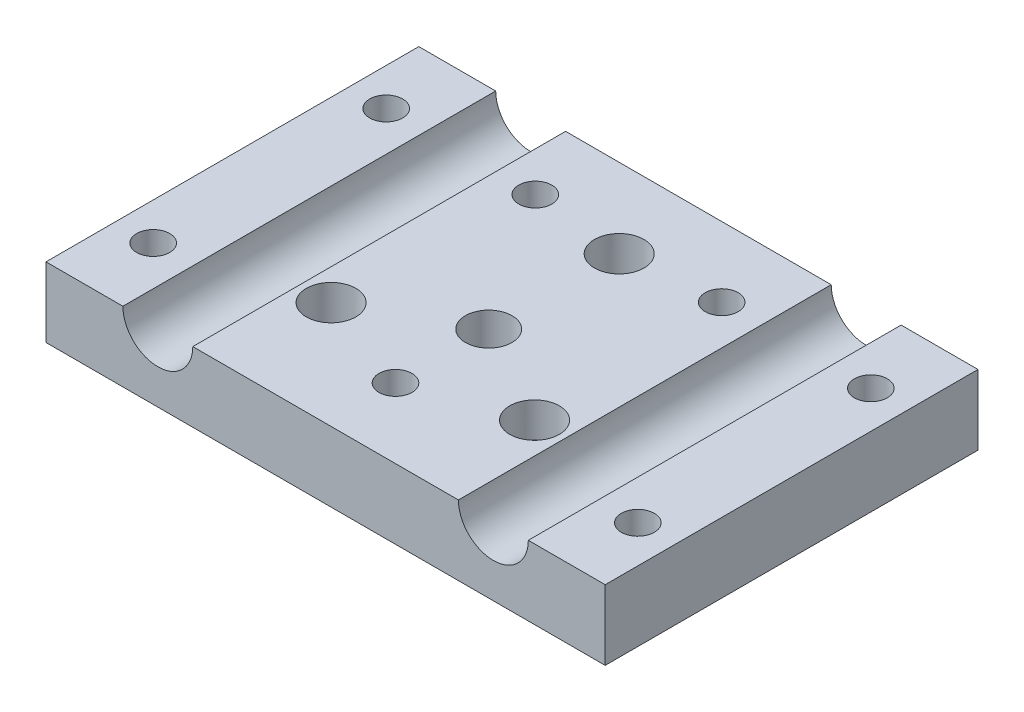
SolidWorks part; units mm, degrees
material "Copper"
ref_plane "Front Plane" through (0, 0, 0) normal (0, 0, 1) x (1, 0, 0)
ref_plane "Top Plane" through (0, 0, 0) normal (0, 1, 0) x (1, 0, 0)
ref_plane "Right Plane" through (0, 0, 0) normal (1, 0, 0) x (0, 0, -1)
sketch "Sketch1" plane through (0, 0, 0) normal (0, 1, 0) x (1, 0, 0)
  line L1 (-38.1, 25.4) -> (38.1, 25.4)
  line L2 (-38.1, 25.4) -> (-38.1, -25.4)
  line L3 (-38.1, -25.4) -> (38.1, -25.4)
  line L4 (38.1, 25.4) -> (38.1, -25.4)
  dimension "D1" = 50.8
  dimension "D2" = 76.2
  dimension "D3" = 38.1
  dimension "D4" = 25.4
extrude "Boss-Extrude1" add sketch "Sketch1" along normal blind 9.525
hole_wizard "1/4 Clearance Hole1" positions "Sketch3" profile "Sketch2" hole size "1/4" standard "ANSI Inch" end condition through all
sketch "Sketch3" plane through (0, 9.525, 0) normal (0, 1, 0) x (1, 0, 0)
  point P0 (0, 14.6101)
  point P2 (-13.8608, -10.7899)
  point P4 (13.8608, -10.7899)
  dimension "D1" = 10.7899
  dimension "D2" = 14.6101
  dimension "D3" = 13.8608
  dimension "D4" = 27.7216
sketch "Sketch2" plane through (0, 9.525, -14.6101) normal (1, 0, 0) x (0, 0, 1)
  line L0 (0, 0) -> (0, 9.525)
  line L1 (0, 9.525) -> (3.3782, 9.525)
  line L2 (3.3782, 9.525) -> (3.3782, 0)
  line L5 (3.3782, 0) -> (0, 0)
  line L11 (0, -6.35) -> (0, 107.95) construction
  dimension "Thru Hole Dia." = 6.7564
  dimension "Thru Hole Depth" = 9.525
sketch "Sketch4" plane through (0, 0, 25.4) normal (0, 0, 1) x (1, 0, 0)
  line L0 (-38.1, 9.525) -> (38.1, 9.525) construction
  line L1 (-27.6225, 9.525) -> (-18.0975, 9.525)
  line L2 (18.0975, 9.525) -> (27.6225, 9.525)
  arc A0 (-27.6225, 9.525) -> (-18.0975, 9.525) centre (-22.86, 9.525) ccw
  arc A1 (18.0975, 9.525) -> (27.6225, 9.525) centre (22.86, 9.525) ccw
  dimension "D1" = 4.7625
  dimension "D2" = 4.7625
  dimension "D3" = 22.86
  dimension "D4" = 22.86
extrude "Cut-Extrude1" cut sketch "Sketch4" against normal through all
sketch "Sketch5" plane through (0, 9.525, 0) normal (0, 1, 0) x (1, 0, 0)
  circle A0 centre (0, -3.175) radius 2.3813
  dimension "D1" = 3.175
  dimension "D2" = 4.7625
extrude "Cut-Extrude2" cut sketch "Sketch5" against normal through all
hole_wizard "#8 Clearance Hole1" positions "Sketch7" profile "Sketch6" hole size "#8" standard "ANSI Inch" end condition through all
sketch "Sketch7" plane through (0, 9.525, 0) normal (0, 1, 0) x (1, 0, 0)
  point P0 (-33.02, 15.875)
  point P2 (-33.02, -15.875)
  point P4 (33.02, -15.875)
  point P6 (33.02, 15.875)
  point P14 (-12.7, 15.875)
  point P16 (12.7, 15.875)
  point P18 (0, -15.875)
  dimension "D1" = 33.02
  dimension "D2" = 15.875
  dimension "D3" = 15.875
  dimension "D4" = 33.02
  dimension "D5" = 12.7
  dimension "D6" = 12.7
sketch "Sketch6" plane through (-33.02, 9.525, -15.875) normal (1, 0, 0) x (0, 0, 1)
  line L0 (0, 0) -> (0, 9.525)
  line L1 (0, 9.525) -> (2.2479, 9.525)
  line L2 (2.2479, 9.525) -> (2.2479, 0)
  line L5 (2.2479, 0) -> (0, 0)
  line L11 (0, -6.35) -> (0, 107.95) construction
  dimension "Thru Hole Dia." = 4.4958
  dimension "Thru Hole Depth" = 9.525
sketch "Sketch8" plane through (0, 0, 0) normal (0, -1, 0) x (1, 0, 0)
  line L0 (-17.2898, 4.8209) -> (-10.4318, 4.8209)
  line L1 (-10.4318, 4.8209) -> (-7.0028, 10.7601)
  line L2 (-7.0028, 10.7601) -> (-10.4318, 16.6993)
  line L3 (-10.4318, 16.6993) -> (-17.2898, 16.6993)
  line L4 (-17.2898, 16.6993) -> (-20.7188, 10.7601)
  line L5 (-20.7188, 10.7601) -> (-17.2898, 4.8209)
  line L6 (10.4318, 4.8209) -> (17.2898, 4.8209)
  line L7 (17.2898, 4.8209) -> (20.7188, 10.7601)
  line L8 (20.7188, 10.7601) -> (17.2898, 16.6993)
  line L9 (17.2898, 16.6993) -> (10.4318, 16.6993)
  line L10 (10.4318, 16.6993) -> (7.0028, 10.7601)
  line L11 (7.0028, 10.7601) -> (10.4318, 4.8209)
  line L12 (-3.429, -20.5791) -> (3.429, -20.5791)
  line L13 (3.429, -20.5791) -> (6.858, -14.6399)
  line L14 (6.858, -14.6399) -> (3.429, -8.7007)
  line L15 (3.429, -8.7007) -> (-3.429, -8.7007)
  line L16 (-3.429, -8.7007) -> (-6.858, -14.6399)
  line L17 (-6.858, -14.6399) -> (-3.429, -20.5791)
  circle A0 centre (-13.8608, 10.7899) radius 3.3782 construction
  circle A1 centre (13.8608, 10.7899) radius 3.3782 construction
  circle A2 centre (0, -14.6101) radius 3.3782 construction
  dimension "D1" = 6.858
  dimension "D2" = 120
  dimension "D3" = 11.8784
  dimension "D4" = 5.969
  dimension "D5" = 13.716
  dimension "D6" = 6.858
  dimension "D7" = 6.858
  dimension "D8" = 120
  dimension "D9" = 11.8784
  dimension "D10" = 5.969
  dimension "D11" = 6.858
  dimension "D12" = 6.858
  dimension "D13" = 120
  dimension "D14" = 11.8784
  dimension "D15" = 5.969
  dimension "D16" = 6.858
extrude "Cut-Extrude3" cut sketch "Sketch8" against normal blind 4.7625
sketch "Sketch9" plane through (0, 0, 0) normal (0, -1, 0) x (1, 0, 0)
  line L0 (-37.465, 13.3087) -> (-37.465, 18.4413)
  line L1 (-37.465, 18.4413) -> (-33.02, 21.0076)
  line L2 (-33.02, 21.0076) -> (-28.575, 18.4413)
  line L3 (-28.575, 18.4413) -> (-28.575, 13.3087)
  line L4 (-28.575, 13.3087) -> (-33.02, 10.7424)
  line L5 (-33.02, 10.7424) -> (-37.465, 13.3087)
  line L6 (-4.445, 13.3087) -> (-4.445, 18.4413)
  line L7 (-4.445, 18.4413) -> (0, 21.0076)
  line L8 (0, 21.0076) -> (4.445, 18.4413)
  line L9 (4.445, 18.4413) -> (4.445, 13.3087)
  line L10 (4.445, 13.3087) -> (0, 10.7424)
  line L11 (0, 10.7424) -> (-4.445, 13.3087)
  line L12 (28.575, 13.3087) -> (28.575, 18.4413)
  line L13 (28.575, 18.4413) -> (33.02, 21.0076)
  line L14 (33.02, 21.0076) -> (37.465, 18.4413)
  line L15 (37.465, 18.4413) -> (37.465, 13.3087)
  line L16 (37.465, 13.3087) -> (33.02, 10.7424)
  line L17 (33.02, 10.7424) -> (28.575, 13.3087)
  line L18 (28.575, -18.4413) -> (28.575, -13.3087)
  line L19 (28.575, -13.3087) -> (33.02, -10.7424)
  line L20 (33.02, -10.7424) -> (37.465, -13.3087)
  line L21 (37.465, -13.3087) -> (37.465, -18.4413)
  line L22 (37.465, -18.4413) -> (33.02, -21.0076)
  line L23 (33.02, -21.0076) -> (28.575, -18.4413)
  line L24 (8.255, -18.4413) -> (8.255, -13.3087)
  line L25 (8.255, -13.3087) -> (12.7, -10.7424)
  line L26 (12.7, -10.7424) -> (17.145, -13.3087)
  line L27 (17.145, -13.3087) -> (17.145, -18.4413)
  line L28 (17.145, -18.4413) -> (12.7, -21.0076)
  line L29 (12.7, -21.0076) -> (8.255, -18.4413)
  line L30 (-17.145, -18.4413) -> (-17.145, -13.3087)
  line L31 (-17.145, -13.3087) -> (-12.7, -10.7424)
  line L32 (-12.7, -10.7424) -> (-8.255, -13.3087)
  line L33 (-8.255, -13.3087) -> (-8.255, -18.4413)
  line L34 (-8.255, -18.4413) -> (-12.7, -21.0076)
  line L35 (-12.7, -21.0076) -> (-17.145, -18.4413)
  line L36 (-37.465, -18.4413) -> (-37.465, -13.3087)
  line L37 (-37.465, -13.3087) -> (-33.02, -10.7424)
  line L38 (-33.02, -10.7424) -> (-28.575, -13.3087)
  line L39 (-28.575, -13.3087) -> (-28.575, -18.4413)
  line L40 (-28.575, -18.4413) -> (-33.02, -21.0076)
  line L41 (-33.02, -21.0076) -> (-37.465, -18.4413)
  circle A0 centre (-33.02, 15.875) radius 2.2479 construction
  circle A1 centre (0, 15.875) radius 2.2479 construction
  circle A2 centre (33.02, 15.875) radius 2.2479 construction
  circle A3 centre (33.02, -15.875) radius 2.2479 construction
  circle A4 centre (12.7, -15.875) radius 2.2479 construction
  circle A5 centre (-12.7, -15.875) radius 2.2479 construction
  circle A6 centre (-33.02, -15.875) radius 2.2479 construction
  dimension "D1" = 120
  dimension "D2" = 8.89
  dimension "D3" = 4.445
  dimension "D4" = 4.445
  dimension "D5" = 120
  dimension "D6" = 8.89
  dimension "D7" = 120
  dimension "D8" = 8.89
  dimension "D9" = 120
  dimension "D10" = 8.89
  dimension "D11" = 120
  dimension "D12" = 8.89
  dimension "D13" = 120
  dimension "D14" = 8.89
  dimension "D15" = 120
  dimension "D16" = 8.89
  dimension "D17" = 4.445
  dimension "D18" = 4.445
  dimension "D19" = 4.445
  dimension "D20" = 4.445
  dimension "D21" = 4.445
  dimension "D22" = 4.445
  dimension "D23" = 4.445
  dimension "D24" = 4.445
  dimension "D25" = 4.445
  dimension "D26" = 4.445
  dimension "D27" = 4.445
  dimension "D28" = 4.445
extrude "Cut-Extrude4" cut sketch "Sketch9" against normal blind 3.175
sketch "Sketch11" plane through (0, 9.525, 0) normal (0, 1, 0) x (1, 0, 0)
  circle A0 centre (0, -3.175) radius 3.175
  dimension "D1" = 6.35
extrude "Cut-Extrude5" cut sketch "Sketch11" against normal blind 6.35
